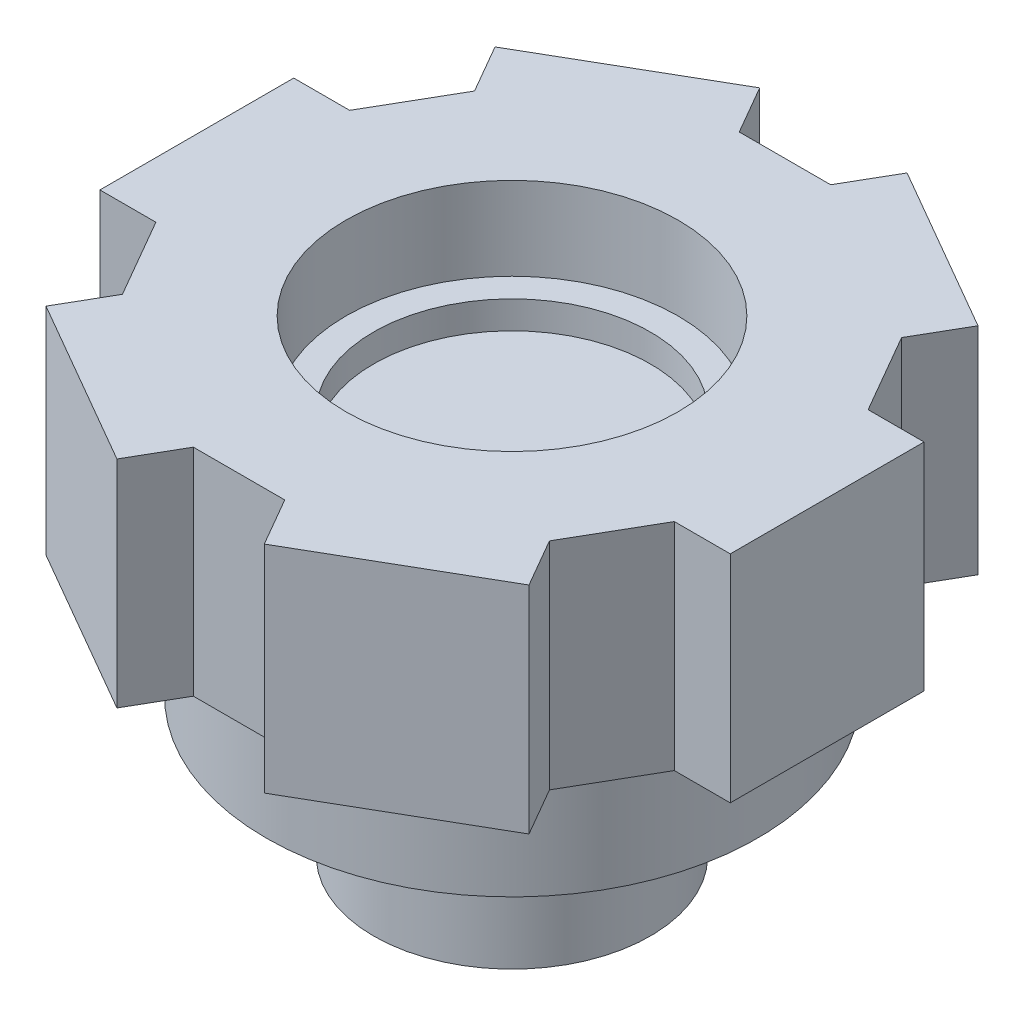
SolidWorks part; units mm, degrees
ref_plane "Front Plane" through (0, 0, 0) normal (0, 0, 1) x (1, 0, 0)
ref_plane "Top Plane" through (0, 0, 0) normal (0, 1, 0) x (1, 0, 0)
ref_plane "Right Plane" through (0, 0, 0) normal (1, 0, 0) x (0, 0, -1)
sketch "Sketch1" plane through (0, 0, 0) normal (0, 1, 0) x (1, 0, 0)
  circle A0 centre (0, 0) radius 5
  dimension "D1" = 10
extrude "Boss-Extrude1" add sketch "Sketch1" along normal blind 5
sketch "Sketch2" plane through (0, 5, 0) normal (0, 1, 0) x (1, 0, 0)
  circle A0 centre (0, 0) radius 8.875
  dimension "D1" = 17.75
extrude "Boss-Extrude2" add sketch "Sketch2" along normal blind 4.11
sketch "Sketch3" plane through (0, 9.11, 0) normal (0, 1, 0) x (1, 0, 0)
  line L0 (9.3643, 3.5) -> (11.385, 3.5)
  line L1 (-1.651, -9.8597) -> (1.651, -9.8597)
  line L2 (7.7132, -6.3597) -> (9.3643, -3.5)
  line L3 (9.3643, 3.5) -> (7.7132, 6.3597)
  line L4 (1.651, 9.8597) -> (-1.651, 9.8597)
  line L5 (-7.7132, 6.3597) -> (-9.3643, 3.5)
  line L6 (-9.3643, -3.5) -> (-7.7132, -6.3597)
  line L7 (11.385, 3.5) -> (11.385, -3.5)
  line L8 (11.385, -3.5) -> (9.3643, -3.5)
  line L9 (7.7132, -6.3597) -> (8.7236, -8.1097)
  line L10 (8.7236, -8.1097) -> (2.6614, -11.6097)
  line L11 (2.6614, -11.6097) -> (1.651, -9.8597)
  line L12 (-1.651, -9.8597) -> (-2.6614, -11.6097)
  line L13 (-2.6614, -11.6097) -> (-8.7236, -8.1097)
  line L14 (-8.7236, -8.1097) -> (-7.7132, -6.3597)
  line L15 (-9.3643, -3.5) -> (-11.385, -3.5)
  line L16 (-11.385, -3.5) -> (-11.385, 3.5)
  line L17 (-11.385, 3.5) -> (-9.3643, 3.5)
  line L18 (-7.7132, 6.3597) -> (-8.7236, 8.1097)
  line L19 (-8.7236, 8.1097) -> (-2.6614, 11.6097)
  line L20 (-2.6614, 11.6097) -> (-1.651, 9.8597)
  line L21 (1.651, 9.8597) -> (2.6614, 11.6097)
  line L22 (2.6614, 11.6097) -> (8.7236, 8.1097)
  line L23 (8.7236, 8.1097) -> (7.7132, 6.3597)
  circle A1 centre (0, 0) radius 9.8597 construction
  point P35 (-0.6257, 0)
  point P36 (0, 0)
  dimension "D2" = 6
  dimension "D3" = 7
extrude "Boss-Extrude3" add sketch "Sketch3" along normal blind 7.79
sketch "Sketch4" plane through (0, 16.9, 0) normal (0, 1, 0) x (1, 0, 0)
  circle A0 centre (0, 0) radius 6
  dimension "D1" = 12
extrude "Cut-Extrude1" cut sketch "Sketch4" against normal blind 3
sketch "Sketch5" plane through (0, 13.9, 0) normal (0, 1, 0) x (1, 0, 0)
  circle A0 centre (0, 0) radius 5
  dimension "D1" = 10
extrude "Cut-Extrude2" cut sketch "Sketch5" against normal blind 1
